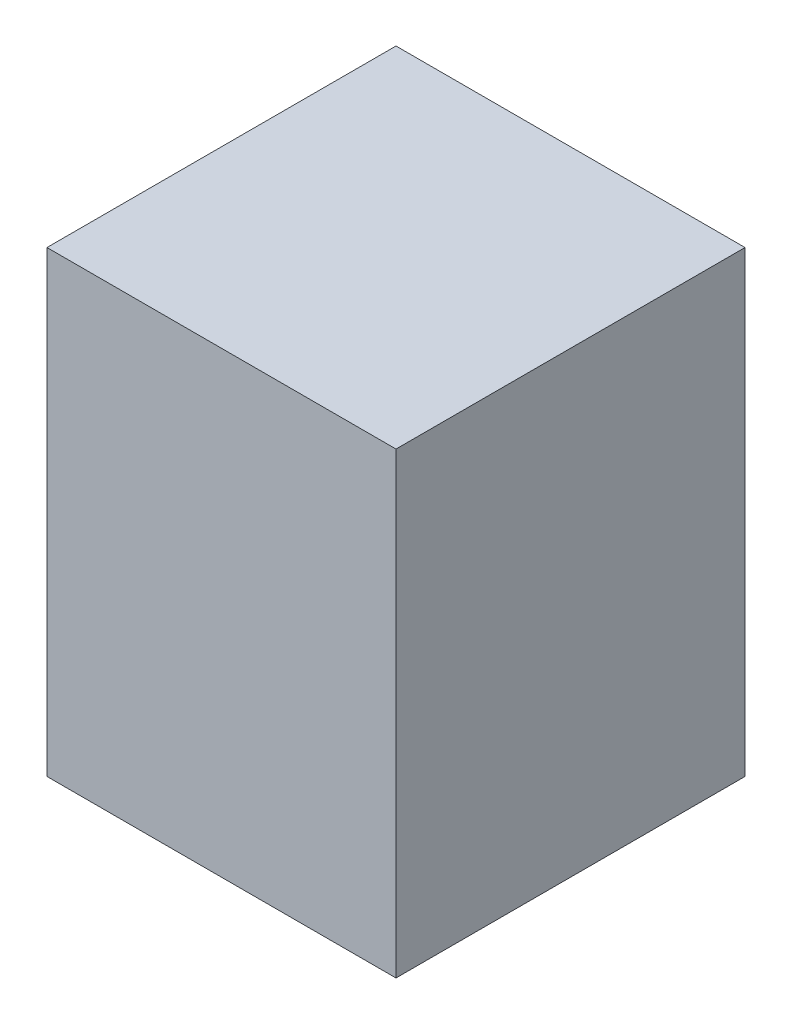
SolidWorks part; units mm, degrees
material "ASTM A36 Steel"
ref_plane "Front Plane" through (0, 0, 0) normal (0, 0, 1) x (1, 0, 0)
ref_plane "Top Plane" through (0, 0, 0) normal (0, 1, 0) x (1, 0, 0)
ref_plane "Right Plane" through (0, 0, 0) normal (1, 0, 0) x (0, 0, -1)
sketch "Sketch1" plane through (0, 0, 0) normal (0, 1, 0) x (1, 0, 0)
  line L1 (-8, -8) -> (8, -8)
  line L2 (-8, -8) -> (-8, 8)
  line L3 (-8, 8) -> (8, 8)
  line L4 (8, -8) -> (8, 8)
  line L5 (-8, -8) -> (8, 8) construction
  line L6 (-8, 8) -> (8, -8) construction
  point P0 (0, 0)
extrude "Boss-Extrude1" add sketch "Sketch1" along normal blind 21
